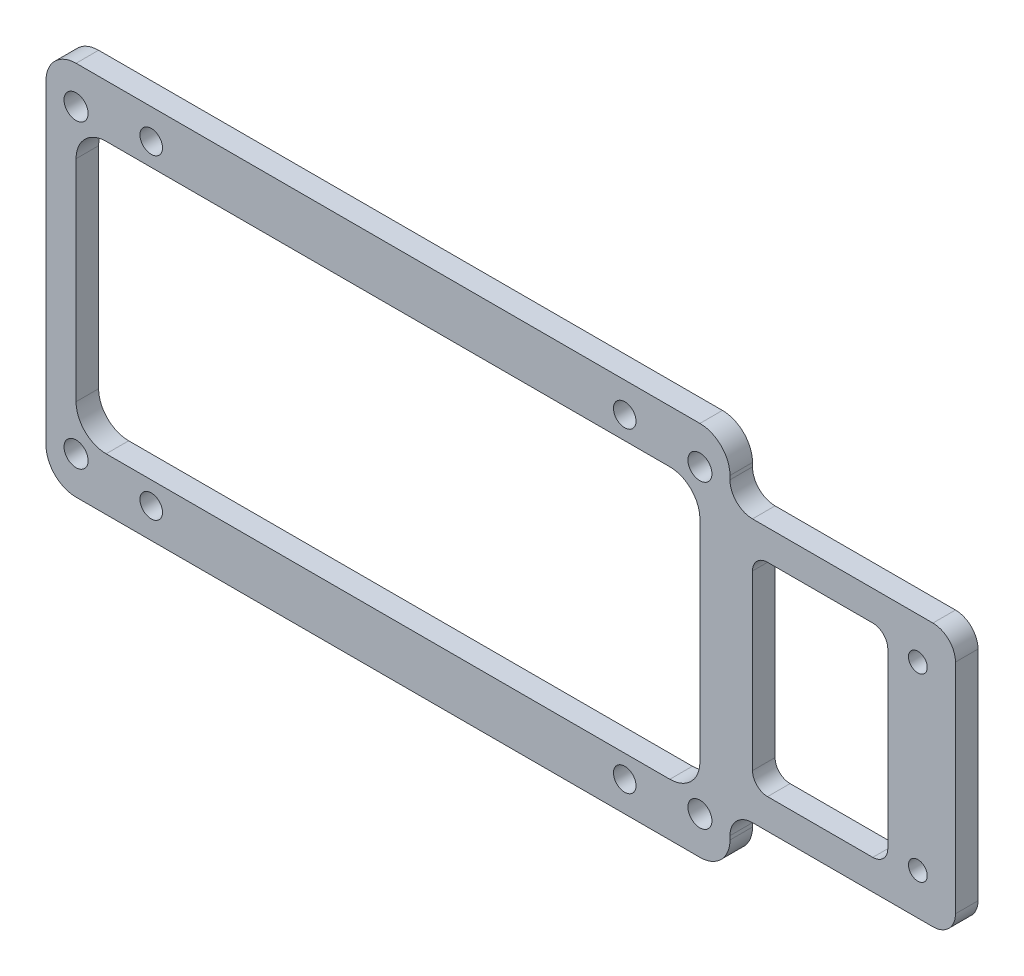
SolidWorks part; units mm, degrees
material "A-玻璃纤维"
ref_plane "前视基准面" through (0, 0, 0) normal (0, 0, 1) x (1, 0, 0)
ref_plane "上视基准面" through (0, 0, 0) normal (0, 1, 0) x (1, 0, 0)
ref_plane "右视基准面" through (0, 0, 0) normal (1, 0, 0) x (0, 0, -1)
sketch "草图1" plane through (0, 0, 0) normal (0, 0, 1) x (1, 0, 0)
  line L1 (-45.5, -25) -> (45.5, -25)
  line L2 (-45.5, -25) -> (-45.5, 25)
  line L3 (-45.5, 25) -> (45.5, 25)
  line L4 (45.5, -25) -> (45.5, 25)
  line L5 (-45.5, -25) -> (45.5, 25) construction
  line L6 (-45.5, 25) -> (45.5, -25) construction
  line L7 (-41.5, -18) -> (41.5, -18)
  line L8 (-41.5, -18) -> (-41.5, 18)
  line L9 (-41.5, 18) -> (41.5, 18)
  line L10 (41.5, -18) -> (41.5, 18)
  line L11 (-41.5, -18) -> (41.5, 18) construction
  line L12 (-41.5, 18) -> (41.5, -18) construction
  point P0 (0, 0)
  point P6 (0, 0)
  dimension "D1" = 50
  dimension "D2" = 91
  dimension "D3" = 36
  dimension "D4" = 83
extrude "凸台-拉伸1" add sketch "草图1" along normal blind 3
sketch "草图2" plane through (0, 0, 3) normal (0, 0, 1) x (1, 0, 0)
  line L1 (-31.5, -21) -> (31.5, -21) construction
  line L2 (-31.5, -21) -> (-31.5, 21) construction
  line L3 (-31.5, 21) -> (31.5, 21) construction
  line L4 (31.5, -21) -> (31.5, 21) construction
  line L5 (-31.5, -21) -> (31.5, 21) construction
  line L6 (-31.5, 21) -> (31.5, -21) construction
  circle A0 centre (31.5, 21) radius 1.5
  circle A1 centre (31.5, -21) radius 1.5
  circle A2 centre (-31.5, -21) radius 1.5
  circle A3 centre (-31.5, 21) radius 1.5
  point P0 (0, 0)
  dimension "D3" = 3
  dimension "D1" = 42
  dimension "D2" = 63
extrude "切除-拉伸1" cut sketch "草图2" against normal blind 3
sketch "草图3" plane through (0, 0, 3) normal (0, 0, 1) x (1, 0, 0)
  line L1 (-41.5, -20) -> (41.5, -20) construction
  line L2 (-41.5, -20) -> (-41.5, 20) construction
  line L3 (-41.5, 20) -> (41.5, 20) construction
  line L4 (41.5, -20) -> (41.5, 20) construction
  line L5 (-41.5, -20) -> (41.5, 20) construction
  line L6 (-41.5, 20) -> (41.5, -20) construction
  circle A0 centre (41.5, 20) radius 1.6
  circle A1 centre (41.5, -20) radius 1.6
  circle A2 centre (-41.5, -20) radius 1.6
  circle A3 centre (-41.5, 20) radius 1.6
  point P0 (0, 0)
  dimension "D3" = 3.2
  dimension "D1" = 83
  dimension "D2" = 40
extrude "切除-拉伸2" cut sketch "草图3" against normal blind 3
fillet "圆角1" radius 4 8 edges at (-41.5, -18, 1.5) (41.5, -18, 1.5) (45.5, -25, 1.5) (-45.5, -25, 1.5) (-45.5, 25, 1.5) (45.5, 25, 1.5) (41.5, 18, 1.5) (-41.5, 18, 1.5)
sketch "草图4" plane through (0, 0, 0) normal (0, 0, -1) x (-1, 0, 0)
  line L0 (-45.5, -21) -> (-45.5, 21) construction
  line L1 (-45.5, 17.5) -> (-75.5, 17.5)
  line L2 (-45.5, 17.5) -> (-45.5, -17.5)
  line L3 (-45.5, -17.5) -> (-75.5, -17.5)
  line L4 (-75.5, 17.5) -> (-75.5, -17.5)
  line L5 (-45.5, 0) -> (0, 0) construction
  dimension "D1" = 35
  dimension "D2" = 30
extrude "凸台-拉伸2" add sketch "草图4" against normal up to surface (3 mm away) up to face at (-39.9, 20, 3)
sketch "草图5" plane through (0, 0, 0) normal (0, 0, -1) x (-1, 0, 0)
  line L0 (-70.5, 17.5) -> (-70.5, -17.5) construction
  line L3 (-70.5, 0) -> (0, 0) construction
  line L4 (-75.5, 17.5) -> (-75.5, -17.5) construction
  circle A0 centre (-70.5, -12) radius 1.25
  circle A1 centre (-70.5, 12) radius 1.25
  dimension "D2" = 2.5
  dimension "D1" = 12
  dimension "D3" = 5
extrude "切除-拉伸3" cut sketch "草图5" against normal blind 10
fillet "圆角2" radius 3 4 edges at (45.5, 17.5, 1.5) (75.5, 17.5, 1.5) (75.5, -17.5, 1.5) (45.5, -17.5, 1.5)
sketch "草图6" plane through (0, 0, 0) normal (0, 0, -1) x (-1, 0, 0)
  line L0 (-48.5, 17.5) -> (-72.5, 17.5) construction
  line L5 (-66.5, 13.5) -> (-48.5, 13.5)
  line L6 (-66.5, 13.5) -> (-66.5, -13.5)
  line L7 (-66.5, -13.5) -> (-48.5, -13.5)
  line L8 (-48.5, 13.5) -> (-48.5, -13.5)
  line L9 (-72.5, -17.5) -> (-48.5, -17.5) construction
  circle A0 centre (-70.5, -12) radius 1.25 construction
  dimension "D1" = 4
  dimension "D2" = 4
  dimension "D3" = 4
  dimension "D4" = 3
extrude "切除-拉伸4" cut sketch "草图6" against normal blind 10
fillet "圆角3" radius 2 4 edges at (48.5, 13.5, 1.5) (48.5, -13.5, 1.5) (66.5, -13.5, 1.5) (66.5, 13.5, 1.5)
sketch "草图7" plane through (0, 0, 0) normal (0, 0, -1) x (-1, 0, 0)
  line L0 (-19, 25) -> (19, 25)
  line L1 (-16, -32) -> (16, -32) construction
  line L2 (-16, -32) -> (-16, 32) construction
  line L3 (-16, 32) -> (16, 32) construction
  line L4 (16, -32) -> (16, 32) construction
  line L5 (0, 32) -> (0, -32) construction
  line L6 (-16, 0) -> (16, 0) construction
  line L7 (-19, -35) -> (19, -35)
  line L8 (-19, -35) -> (-19, -25)
  line L9 (-19, 35) -> (19, 35)
  line L10 (19, -35) -> (19, -25)
  line L11 (0, 35) -> (0, -35) construction
  line L12 (-19, 0) -> (19, 0) construction
  line L13 (-41.5, 25) -> (41.5, 25) construction
  line L14 (-19, -25) -> (19, -25)
  line L15 (41.5, -25) -> (-41.5, -25) construction
  line L16 (19, 25) -> (19, 35)
  line L17 (-19, 25) -> (-19, 35)
  circle A0 centre (16, -32) radius 1.6
  circle A1 centre (-16, -32) radius 1.6
  circle A2 centre (-16, 32) radius 1.6
  circle A3 centre (16, 32) radius 1.6
  point P0 (0, 0)
  point P4 (0, 0)
  dimension "D6" = 3.2
  dimension "D1" = 64
  dimension "D2" = 32
  dimension "D3" = 38
  dimension "D4" = 3
  dimension "D5" = 3
extrude "凸台-拉伸3" add sketch "草图7" against normal up to surface (3 mm away) up to face at (57.5, 0, 3)
fillet "圆角4" radius 2 4 edges at (-19, -35, 1.5) (19, -35, 1.5) (-19, 35, 1.5) (19, 35, 1.5)
fillet "圆角5" radius 2 4 edges at (-19, -25, 1.5) (19, -25, 1.5) (19, 25, 1.5) (-19, 25, 1.5)
sketch "草图8" plane through (0, 0, 3) normal (0, 0, 1) x (1, 0, 0)
  line L0 (17, 35) -> (-17, 35) construction
  line L1 (-21, 25) -> (21, 25)
  line L2 (-21, 25) -> (-21, 35)
  line L3 (-21, 35) -> (21, 35)
  line L4 (21, 25) -> (21, 35)
  line L5 (-17, -35) -> (17, -35) construction
  line L6 (-21, -25) -> (21, -25)
  line L7 (-21, -25) -> (-21, -35)
  line L8 (-21, -35) -> (21, -35)
  line L9 (21, -25) -> (21, -35)
  point P4 (21, -25)
extrude "切除-拉伸5" cut sketch "草图8" against normal blind 10
